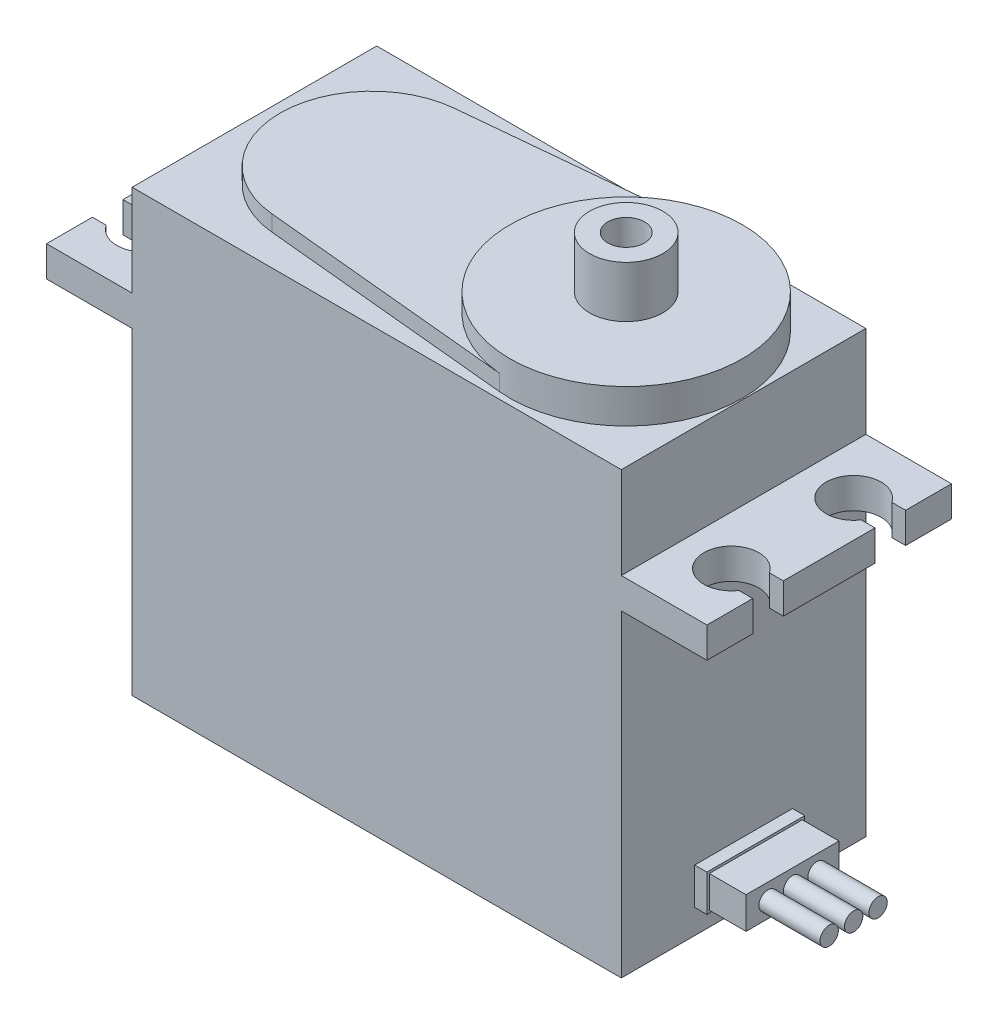
SolidWorks part; units mm, degrees
ref_plane "정면" through (0, 0, 0) normal (0, 0, 1) x (1, 0, 0)
ref_plane "윗면" through (0, 0, 0) normal (0, 1, 0) x (1, 0, 0)
ref_plane "우측면" through (0, 0, 0) normal (1, 0, 0) x (0, 0, -1)
sketch "스케치1" plane through (0, 0, 0) normal (0, 1, 0) x (1, 0, 0)
  line L1 (-20, 10) -> (20, 10)
  line L2 (-20, 10) -> (-20, -10)
  line L3 (-20, -10) -> (20, -10)
  line L4 (20, 10) -> (20, -10)
  line L5 (-20, 10) -> (20, -10) construction
  line L6 (-20, -10) -> (20, 10) construction
  point P0 (0, 0)
  dimension "D1" = 40
  dimension "D2" = 20
extrude "보스-돌출1" add sketch "스케치1" along normal blind 26
sketch "스케치2" plane through (0, 26, 0) normal (0, 1, 0) x (1, 0, 0)
  line L0 (-24, 10) -> (-24, -10) construction
  line L1 (-27, 10) -> (27, 10)
  line L2 (-27, 10) -> (-27, 6.25)
  line L3 (-27, -10) -> (27, -10)
  line L4 (27, 10) -> (27, 6.25)
  line L5 (-27, 10) -> (27, -10) construction
  line L6 (-27, -10) -> (27, 10) construction
  line L7 (24, 10) -> (24, -10) construction
  line L8 (-27, 3.75) -> (-27, -3.75)
  line L9 (-25.8708, 3.75) -> (-27, 3.75)
  line L11 (-25.8708, 6.25) -> (-27, 6.25)
  line L13 (-27, -6.25) -> (-27, -10)
  line L14 (-25.8708, -6.25) -> (-27, -6.25)
  line L15 (-27, 10) -> (-27, -10) construction
  line L17 (-25.8708, -3.75) -> (-27, -3.75)
  line L19 (27, 3.75) -> (27, -3.75)
  line L20 (25.8686, 3.75) -> (27, 3.75)
  line L22 (25.8686, 6.25) -> (27, 6.25)
  line L24 (27, -6.25) -> (27, -10)
  line L26 (25.8662, -6.25) -> (27, -6.25)
  line L28 (25.8662, -3.75) -> (27, -3.75)
  line L32 (27, 10) -> (27, -10) construction
  arc A0 (-25.8708, 3.75) -> (-25.8708, 6.25) centre (-24, 5) ccw
  arc A1 (-25.8708, -6.25) -> (-25.8708, -3.75) centre (-24, -5) ccw
  arc A2 (25.8662, -3.75) -> (25.8662, -6.25) centre (24, -5) ccw
  arc A3 (25.8686, 6.25) -> (25.8686, 3.75) centre (24, 5) ccw
  point P0 (0, 0)
  point P34 (0, 0)
  point P35 (0, 0)
  dimension "D4" = 5
  dimension "D5" = 5
  dimension "D6" = 4.5
  dimension "D7" = 4.5
  dimension "D9" = 5
  dimension "D10" = 5
  dimension "D12" = 20
  dimension "D1" = 54
  dimension "D13" = 2.5
  dimension "D14" = 1.25
  dimension "D2" = 3
  dimension "D3" = 3
extrude "보스-돌출2" add sketch "스케치2" along normal blind 2.5
sketch "스케치3" plane through (0, 28.5, 0) normal (0, 1, 0) x (1, 0, 0)
  line L0 (27, 10) -> (-27, 10) construction
  line L1 (-20, -10) -> (20, -10)
  line L2 (-20, -10) -> (-20, 10)
  line L3 (-20, 10) -> (20, 10)
  line L4 (20, -10) -> (20, 10)
  line L5 (-20, -10) -> (20, 10) construction
  line L6 (-20, 10) -> (20, -10) construction
  point P0 (0, 0)
  dimension "D1" = 40
extrude "보스-돌출3" add sketch "스케치3" along normal blind 7.5
sketch "스케치4" plane through (0, 36, 0) normal (0, 1, 0) x (1, 0, 0)
  line L0 (20, -10) -> (20, 10) construction
  line L1 (-20, 10) -> (-20, -10) construction
  line L4 (-11.1059, 7.4667) -> (9.4866, 9.456)
  line L5 (-11.106, -7.4667) -> (9.4865, -9.456)
  arc A0 (9.4865, -9.456) -> (9.4866, 9.456) centre (10.4, 0) ccw
  arc A1 (-11.1059, 7.4667) -> (-11.106, -7.4667) centre (-10.4, 0) ccw
  dimension "D1" = 19
  dimension "D2" = 9.6
  dimension "D3" = 9.6
  dimension "D4" = 15
extrude "보스-돌출4" add sketch "스케치4" along normal blind 1.3
sketch "스케치5" plane through (0, 37.3, 0) normal (0, 1, 0) x (1, 0, 0)
  circle A0 centre (10.4, 0) radius 9.5
extrude "보스-돌출5" add sketch "스케치5" along normal blind 1.5
sketch "스케치6" plane through (0, 38.8, 0) normal (0, 1, 0) x (1, 0, 0)
  circle A0 centre (10.4, 0) radius 3
  dimension "D1" = 6
extrude "보스-돌출6" add sketch "스케치6" along normal blind 4.2
sketch "스케치7" plane through (20, 0, 0) normal (1, 0, 0) x (0, 0, -1)
  line L0 (0, 0) -> (0, 6.5576) construction
  line L3 (-4, 5) -> (4, 5)
  line L4 (-4, 5) -> (-4, 2)
  line L5 (-4, 2) -> (4, 2)
  line L6 (4, 5) -> (4, 2)
  line L7 (-4, 5) -> (4, 2) construction
  line L8 (-4, 2) -> (4, 5) construction
  line L9 (-10, 0) -> (10, 0) construction
  point P0 (0, 3.5)
  point P7 (0, 2.7124)
  dimension "D1" = 8
  dimension "D2" = 3
  dimension "D3" = 2
extrude "보스-돌출7" add sketch "스케치7" along normal blind 1
sketch "스케치8" plane through (21, 0, 0) normal (1, 0, 0) x (0, 0, -1)
  line L0 (-4, 5) -> (-4, 2) construction
  line L1 (-3.8, 4.8) -> (3.8, 4.8)
  line L2 (-3.8, 4.8) -> (-3.8, 2.2)
  line L3 (-3.8, 2.2) -> (3.8, 2.2)
  line L4 (3.8, 4.8) -> (3.8, 2.2)
  line L5 (-3.8, 4.8) -> (3.8, 2.2) construction
  line L6 (-3.8, 2.2) -> (3.8, 4.8) construction
  line L7 (4, 5) -> (-4, 5) construction
  line L8 (4, 2) -> (4, 5) construction
  line L9 (-4, 2) -> (4, 2) construction
  point P0 (0, 3.5)
  point P7 (-4, 3.5)
  dimension "D1" = 0.2
  dimension "D2" = 0.2
  dimension "D3" = 0.2
  dimension "D4" = 0.2
extrude "보스-돌출8" add sketch "스케치8" along normal blind 3
sketch "스케치9" plane through (24, 0, 0) normal (1, 0, 0) x (0, 0, -1)
  line L0 (0, 0) -> (0, 6.201) construction
  circle A0 centre (0, 3.5051) radius 0.75
  circle A1 centre (-2, 3.4994) radius 0.75
  circle A2 centre (2, 3.5005) radius 0.75
  point P9 (0, 3.4994)
  dimension "D1" = 1.5
  dimension "D2" = 2
  dimension "D3" = 2
extrude "보스-돌출9" add sketch "스케치9" along normal blind 5
sketch "스케치10" plane through (0, 43, 0) normal (0, 1, 0) x (1, 0, 0)
  circle A0 centre (10.4, 0) radius 1.5
  dimension "D1" = 3
extrude "컷-돌출1" cut sketch "스케치10" against normal blind 3
